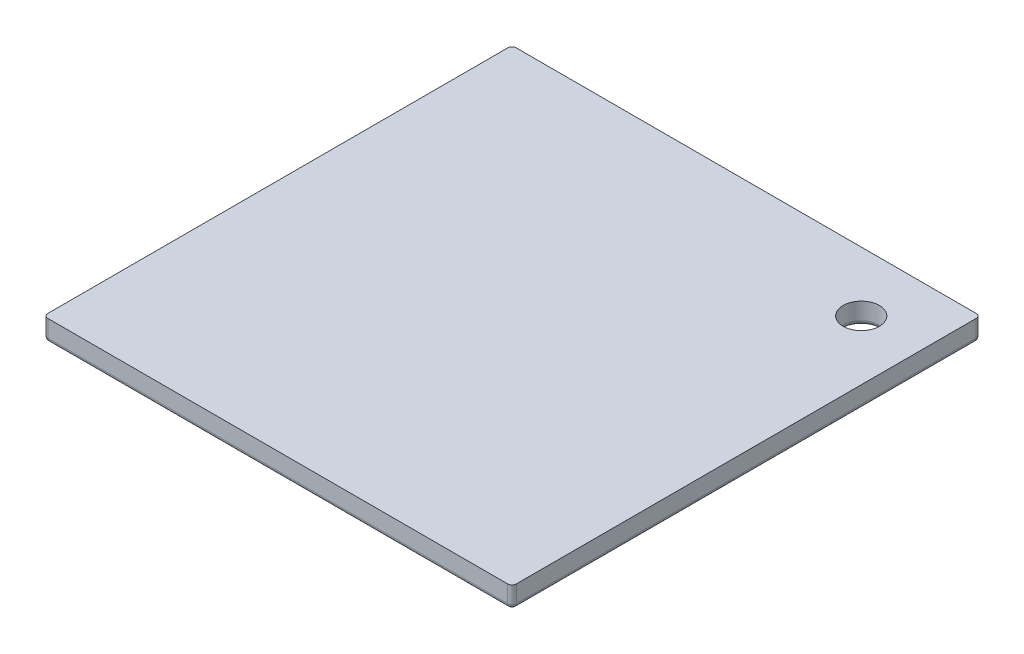
SolidWorks part; units mm, degrees
ref_plane "Front Plane" through (0, 0, 0) normal (0, 0, 1) x (1, 0, 0)
ref_plane "Top Plane" through (0, 0, 0) normal (0, 1, 0) x (1, 0, 0)
ref_plane "Right Plane" through (0, 0, 0) normal (1, 0, 0) x (0, 0, -1)
sketch "Sketch1" plane through (0, 0, 0) normal (0, 1, 0) x (1, 0, 0)
  line L1 (-110, 110) -> (110, 110)
  line L2 (-110, 110) -> (-110, -110)
  line L3 (-110, -110) -> (110, -110)
  line L4 (110, 110) -> (110, -110)
  line L5 (-110, 110) -> (110, -110) construction
  line L6 (-110, -110) -> (110, 110) construction
  line L7 (-97, 97) -> (97, 97)
  line L8 (-97, 97) -> (-97, -97)
  line L9 (-97, -97) -> (97, -97)
  line L10 (97, 97) -> (97, -97)
  line L11 (-97, 97) -> (97, -97) construction
  line L12 (-97, -97) -> (97, 97) construction
  circle A0 centre (82, 82) radius 8.5
  point P0 (0, 0)
  point P6 (0, 0)
  dimension "D7" = 17
  dimension "D1" = 220
  dimension "D2" = 220
  dimension "D3" = 194
  dimension "D4" = 194
  dimension "D5" = 28
extrude "Boss-Extrude1" add sketch "Sketch1" along normal blind 10 contours L4 L1 L2 L3 L7 L10 L9 L8 | L10 L7 L8 L9 A0
fillet "Fillet1" radius 2 4 edges at (-110, 5, 110) (-110, 5, -110) (110, 5, -110) (110, 5, 110)
fillet "Fillet2" radius 2 9 edges at (82, 0, -73.5) (109.4142, 0, 109.4142) (110, 0, 0) (109.4142, 0, -109.4142) (0, 0, -110) (-109.4142, 0, -109.4142) (-110, 0, 0) (-109.4142, 0, 109.4142) (0, 0, 110)
